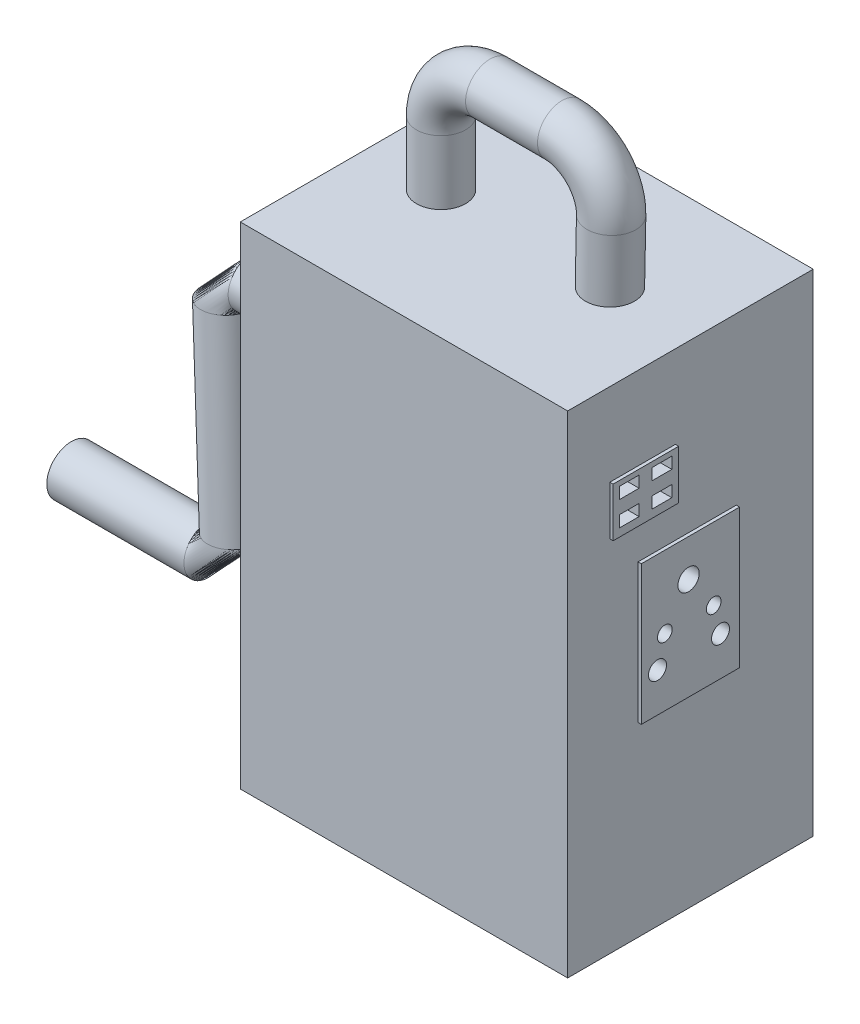
SolidWorks part; units mm, degrees
material "PET"
ref_plane "Front Plane" through (0, 0, 0) normal (0, 0, 1) x (1, 0, 0)
ref_plane "Top Plane" through (0, 0, 0) normal (0, 1, 0) x (1, 0, 0)
ref_plane "Right Plane" through (0, 0, 0) normal (1, 0, 0) x (0, 0, -1)
sketch "Sketch1" plane through (0, 0, 0) normal (0, 1, 0) x (1, 0, 0)
  line L1 (0, 0) -> (200, 0)
  line L2 (0, 0) -> (0, 150)
  line L3 (0, 150) -> (200, 150)
  line L4 (200, 0) -> (200, 150)
  dimension "D1" = 200
  dimension "D2" = 150
extrude "Boss-Extrude1" add sketch "Sketch1" along normal blind 300
sketch "Sketch2" plane through (0, 0, 0) normal (0, -1, 0) x (1, 0, 0)
  line L0 (0, -150) -> (0, 0) construction
  line L1 (0, 0) -> (200, 0) construction
  circle A0 centre (30, -30) radius 10
  dimension "D2" = 20
  dimension "D1" = 30
  dimension "D3" = 30
extrude "Boss-Extrude2" add sketch "Sketch2" along normal blind 10
pattern_linear "LPattern1" count 2 spacing 135 along (1, 0, 0) count 2 spacing 95 along (0, 0, -1) of "Boss-Extrude2"
sketch "Sketch3" plane through (200, 0, 0) normal (1, 0, 0) x (0, 0, -1)
  line L0 (0, 300) -> (0, 0) construction
  line L1 (43, 198.6593) -> (103, 198.6593)
  line L2 (43, 198.6593) -> (43, 113.6593)
  line L3 (43, 113.6593) -> (103, 113.6593)
  line L4 (103, 198.6593) -> (103, 113.6593)
  dimension "D1" = 60
  dimension "D2" = 85
  dimension "D3" = 43
extrude "Boss-Extrude3" add sketch "Sketch3" along normal blind 2
sketch "Sketch4" plane through (202, 0, 0) normal (1, 0, 0) x (0, 0, -1)
  circle A0 centre (71.853, 175.9434) radius 6.5
  circle A1 centre (57.3567, 154.5675) radius 4.5
  circle A2 centre (87.2122, 154.5675) radius 4.5
  circle A3 centre (52.8698, 137.4592) radius 5.5
  circle A4 centre (91.354, 137.4592) radius 5.5
  point P10 (57.3567, 154.5675)
  point P11 (87.2122, 154.5675)
  point P12 (71.853, 175.9434)
  point P13 (52.8698, 137.4592)
  point P14 (91.354, 137.4592)
  dimension "D1" = 13
  dimension "D2" = 9
  dimension "D3" = 9
  dimension "D4" = 11
  dimension "D5" = 11
extrude "Cut-Extrude1" cut sketch "Sketch4" against normal blind 10
sketch "Sketch5" plane through (200, 0, 0) normal (1, 0, 0) x (0, 0, -1)
  line L1 (25.7571, 249.4163) -> (65.7571, 249.4163)
  line L2 (25.7571, 249.4163) -> (25.7571, 219.4163)
  line L3 (25.7571, 219.4163) -> (65.7571, 219.4163)
  line L4 (65.7571, 249.4163) -> (65.7571, 219.4163)
  dimension "D1" = 30
  dimension "D2" = 40
extrude "Boss-Extrude4" add sketch "Sketch5" along normal blind 2
sketch "Sketch6" plane through (202, 0, 0) normal (1, 0, 0) x (0, 0, -1)
  line L1 (29.6212, 246.2893) -> (41.6212, 246.2893)
  line L2 (29.6212, 246.2893) -> (29.6212, 239.2893)
  line L3 (29.6212, 239.2893) -> (41.6212, 239.2893)
  line L4 (41.6212, 246.2893) -> (41.6212, 239.2893)
  dimension "D1" = 7
  dimension "D2" = 12
extrude "Cut-Extrude2" cut sketch "Sketch6" against normal blind 10
pattern_linear "LPattern2" count 2 spacing 20 along (0, 0, -1) count 2 spacing 15 along (0, -1, 0) of "Cut-Extrude2"
sketch "Sketch7" plane through (0, 300, 0) normal (0, 1, 0) x (1, 0, 0)
  point P0 (44.1834, 78.4468)
  point P1 (147.365, 78.4468)
sketch3d "3DSketch2"
  line L0 (44.1834, 300, -78.4468) -> (44.1834, 339.0579, -78.4468)
  line L1 (74.1834, 369.0579, -78.4468) -> (118.1292, 369.0579, -78.4468)
  line L2 (148.1233, 338.4666, -78.4468) -> (147.365, 300, -78.4468)
  arc A0 (118.1292, 369.0579, -78.4468) -> (148.1233, 338.4666, -78.4468) centre (118.1292, 339.0579, -78.4468) ccw
  arc A1 (44.1834, 339.0579, -78.4468) -> (74.1834, 369.0579, -78.4468) centre (74.1834, 339.0579, -78.4468) ccw
  point P6 (149.4121, 403.843, -78.4468)
  point P9 (148.7264, 369.0579, -78.4468)
  point P10 (118.1292, 339.0579, -108.4468)
  point P13 (44.1834, 369.0579, -78.4468)
  point P14 (74.1834, 339.0579, -108.4468)
  dimension "D1" = 30
sweep "Sweep1" add path "3DSketch2" circular profile diameter 30 parameters "D3"=30
sketch "Sketch32" plane through (0, 0, 0) normal (-1, 0, 0) x (0, 0, 1)
  point P0 (-76.4035, 196.2919)
sketch3d "3DSketch4"
  line L0 (0, 196.2919, -76.4035) -> (-68.8086, 196.2919, -76.4035)
  line L1 (-83.7649, 180.1609, -75.7496) -> (-74.7926, 62.9827, -70.9997)
  line L2 (-89.7489, 46.8517, -70.3458) -> (-173.5575, 46.8517, -70.3458)
  arc A0 (-68.8086, 196.2919, -76.4035) -> (-83.7649, 180.1609, -75.7496) centre (-68.8086, 181.3042, -75.7959) ccw
  arc A1 (-74.7926, 62.9827, -70.9997) -> (-89.7489, 46.8517, -70.3458) centre (-89.7489, 61.8394, -70.9533) ccw
  point P6 (-85, 196.2919, -76.4035)
  point P7 (-68.8086, 181.9118, -60.8082)
  point P11 (-73.5575, 46.8517, -70.3458)
  point P12 (-89.7489, 61.2319, -85.941)
  point P13 (0, 0, 0)
  point P14 (-3.1668, 42.603, -88.7716)
  point P15 (-38.402, 35.1019, -78.3197)
  point P16 (-35.9376, 196.2919, -76.4035)
  point P17 (-86.8971, 8.351, -78.9065)
  point P18 (-28.6136, 196.2919, -76.4035)
  point P19 (-121.5092, 3.2066, -68.5766)
  dimension "D1" = 15
  dimension "D3" = 15
  dimension "D2" = 150
  dimension "D4" = 100
  dimension "D5" = 85
sweep "Sweep3" add path "3DSketch4" circular profile diameter 30 parameters "D3"=30
